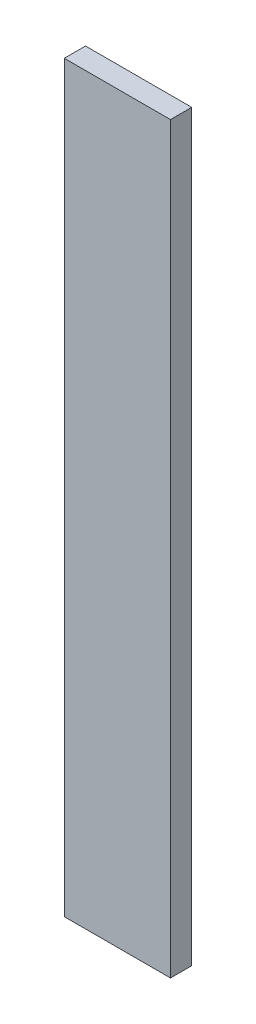
SolidWorks part; units mm, degrees
ref_plane "Front Plane" through (0, 0, 0) normal (0, 0, 1) x (1, 0, 0)
ref_plane "Top Plane" through (0, 0, 0) normal (0, 1, 0) x (1, 0, 0)
ref_plane "Right Plane" through (0, 0, 0) normal (1, 0, 0) x (0, 0, -1)
sketch "Sketch1" plane through (0, 0, 0) normal (0, 1, 0) x (1, 0, 0)
  line L1 (12.7, -2.54) -> (-12.7, -2.54)
  line L2 (12.7, -2.54) -> (12.7, 2.54)
  line L3 (12.7, 2.54) -> (-12.7, 2.54)
  line L4 (-12.7, -2.54) -> (-12.7, 2.54)
  line L5 (12.7, -2.54) -> (-12.7, 2.54) construction
  line L6 (12.7, 2.54) -> (-12.7, -2.54) construction
  point P0 (0, 0)
extrude "Boss-Extrude1" add sketch "Sketch1" along normal blind 177.8
